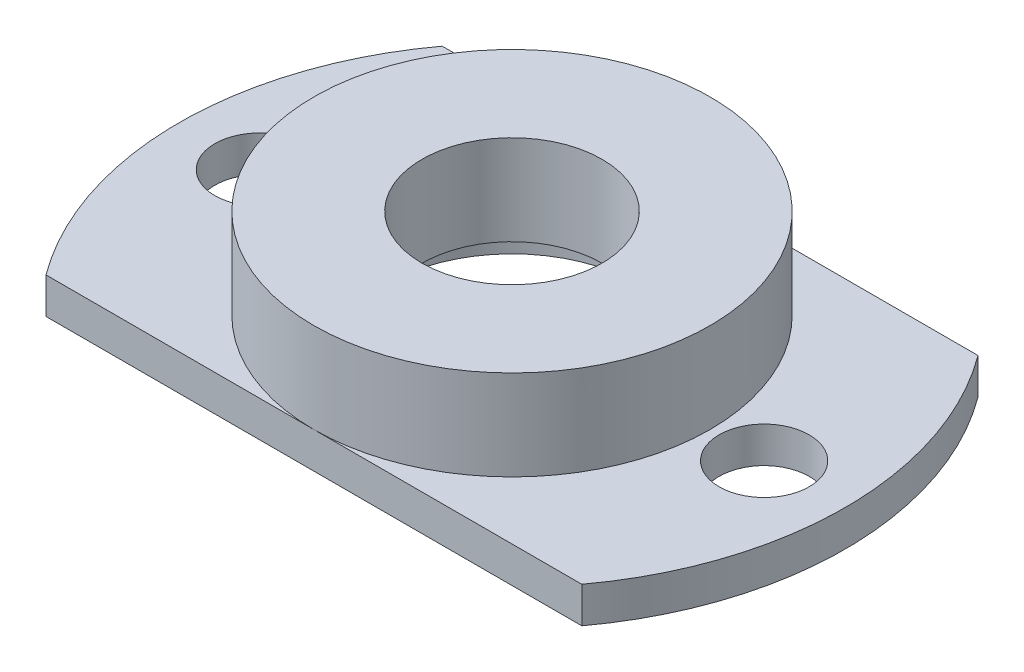
SolidWorks part; units mm, degrees
ref_plane "前视基准面" through (0, 0, 0) normal (0, 0, 1) x (1, 0, 0)
ref_plane "上视基准面" through (0, 0, 0) normal (0, 1, 0) x (1, 0, 0)
ref_plane "右视基准面" through (0, 0, 0) normal (1, 0, 0) x (0, 0, -1)
sketch "草图1" plane through (0, 0, 0) normal (0, 1, 0) x (1, 0, 0)
  line L0 (-14.8745, 11) -> (14.8745, 11)
  line L1 (-14.8745, -11) -> (14.8745, -11)
  arc A0 (-14.8745, 11) -> (-14.8745, -11) centre (0, 0) ccw
  circle A1 centre (0, 0) radius 5
  arc A2 (14.8745, -11) -> (14.8745, 11) centre (0, 0) ccw
  dimension "D1" = 37
  dimension "D2" = 10
  dimension "D3" = 11
  dimension "D4" = 11
extrude "凸台-拉伸1" add sketch "草图1" along normal blind 2
sketch "草图2" plane through (0, 2, 0) normal (0, 1, 0) x (1, 0, 0)
  circle A0 centre (0, 0) radius 11
  circle A1 centre (0, 0) radius 5
  dimension "D1" = 22
extrude "凸台-拉伸2" add sketch "草图2" along normal blind 5
sketch "草图3" plane through (0, 0, 0) normal (0, -1, 0) x (1, 0, 0)
  circle A0 centre (-14, 0) radius 2.5
  circle A2 centre (14, 0) radius 2.5
  dimension "D1" = 5
  dimension "D2" = 28
  dimension "D3" = 14
extrude "切除-拉伸1" cut sketch "草图3" against normal through all
sketch "草图4" plane through (0, 0, 0) normal (0, -1, 0) x (1, 0, 0)
  circle A0 centre (0, 0) radius 7
  dimension "D1" = 14
extrude "切除-拉伸2" cut sketch "草图4" against normal blind 2
